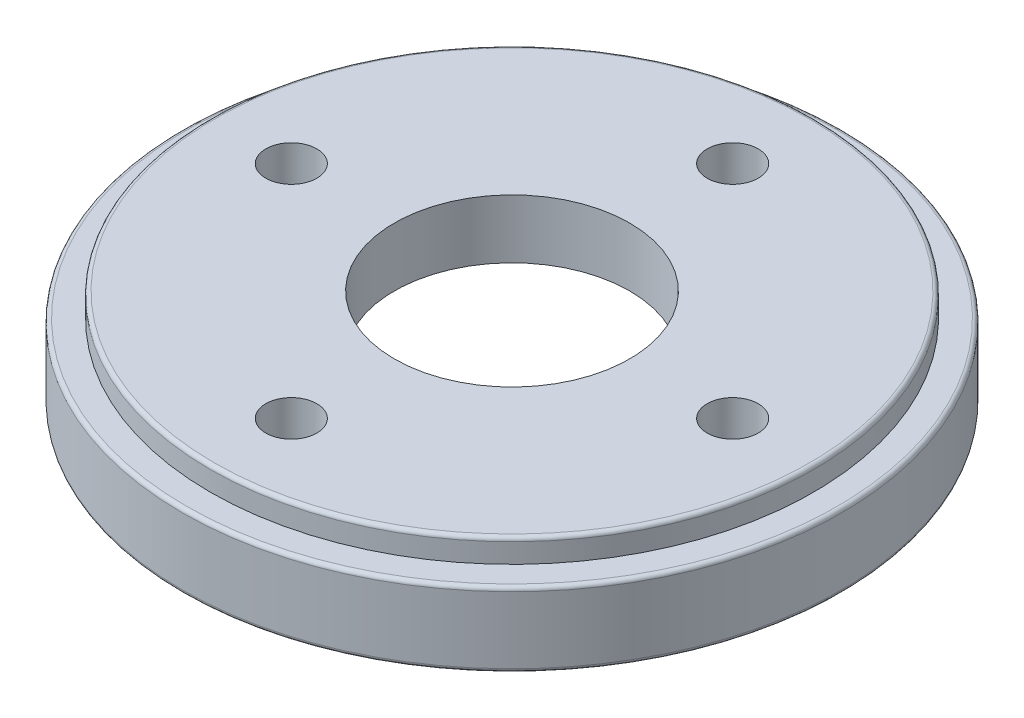
SolidWorks part; units mm, degrees
ref_plane "前视基准面" through (0, 0, 0) normal (0, 0, 1) x (1, 0, 0)
ref_plane "上视基准面" through (0, 0, 0) normal (0, 1, 0) x (1, 0, 0)
ref_plane "右视基准面" through (0, 0, 0) normal (1, 0, 0) x (0, 0, -1)
sketch "草图1" plane through (0, 0, 0) normal (0, 1, 0) x (1, 0, 0)
  circle A0 centre (0, 0) radius 16.8
  circle A1 centre (0, 11.25) radius 1.3
  circle A2 centre (11.25, 0) radius 1.3
  circle A3 centre (0, -11.25) radius 1.3
  circle A4 centre (-11.25, 0) radius 1.3
  circle A5 centre (0, 0) radius 6
  point P14 (0, 0)
  dimension "D1" = 33.6
  dimension "D2" = 2.6
  dimension "D5" = 12
  dimension "D3" = 11.25
  dimension "D4" = 4
extrude "凸台-拉伸1" add sketch "草图1" along normal blind 5
sketch "草图2" plane through (0, 5, 0) normal (0, 1, 0) x (1, 0, 0)
  circle A2 centre (0, 0) radius 15.375
  circle A3 centre (0, 0) radius 16.8 construction
  circle A4 centre (0, 0) radius 16.8
  dimension "D1" = 30.75
extrude "切除-拉伸1" cut sketch "草图2" against normal blind 1.2
fillet "圆角1" radius 0.2 2 edges at (0, 3.8, 16.8) (0, 5, 15.375)
sketch "草图3" plane through (0, 0, 0) normal (0, -1, 0) x (1, 0, 0)
  circle A0 centre (0, 0) radius 16.8 construction
  circle A1 centre (0, 0) radius 16.8 construction
  circle A2 centre (0, 0) radius 14.8
  dimension "D1" = 2
extrude "切除-拉伸2" cut sketch "草图3" against normal blind 2
fillet "圆角2" radius 0.2 1 edges at (0, 0, 16.8)
